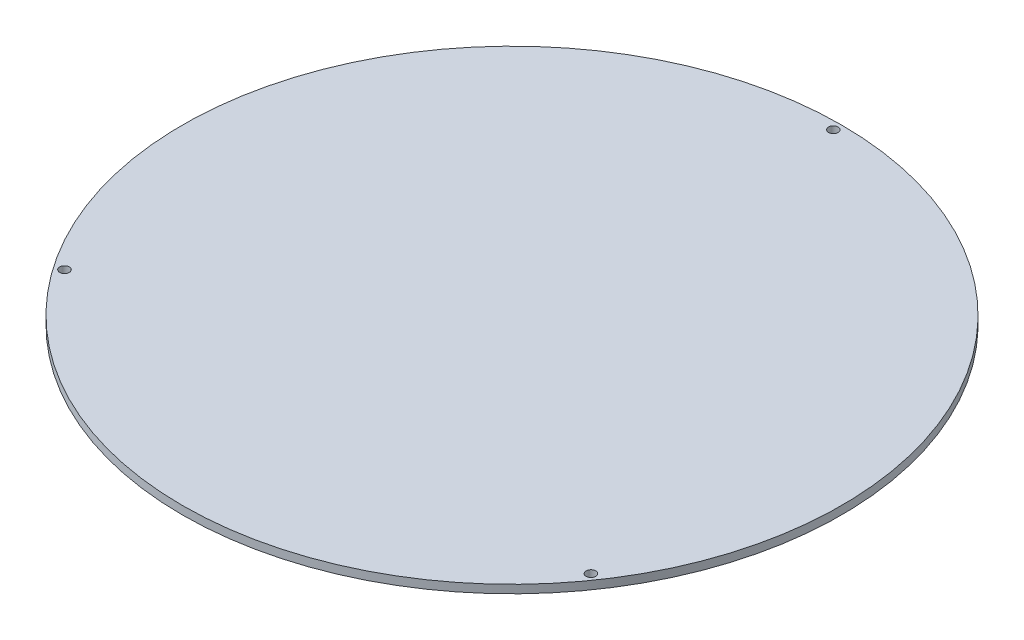
SolidWorks part; units mm, degrees
material "1060 Alloy"
ref_plane "Front Plane" through (0, 0, 0) normal (0, 0, 1) x (1, 0, 0)
ref_plane "Top Plane" through (0, 0, 0) normal (0, 1, 0) x (1, 0, 0)
ref_plane "Right Plane" through (0, 0, 0) normal (1, 0, 0) x (0, 0, -1)
sketch "Sketch1" plane through (0, 0, 0) normal (0, 1, 0) x (1, 0, 0)
  circle A0 centre (0, 0) radius 120
  dimension "D1" = 240
extrude "Boss-Extrude1" add sketch "Sketch1" along normal blind 3
sketch "Sketch2" plane through (0, 0, 0) normal (0, 1, 0) x (1, 0, 0)
  line L0 (0, 0) -> (0, 120) construction
  line L1 (0, 0) -> (98.2982, -68.8292) construction
  line L2 (0, 0) -> (-98.2982, -68.8292) construction
  circle A0 centre (0, 0) radius 120 construction
  circle A1 centre (0, 117) radius 1.75
  circle A2 centre (-95.8408, -67.1084) radius 1.75
  circle A3 centre (95.8408, -67.1084) radius 1.75
  dimension "D3" = 3.5
  dimension "D1" = 125
  dimension "D2" = 125
  dimension "D4" = 3
  dimension "D5" = 3
  dimension "D6" = 3
extrude "Cut-Extrude2" cut sketch "Sketch2" against normal through all and the other way through all
